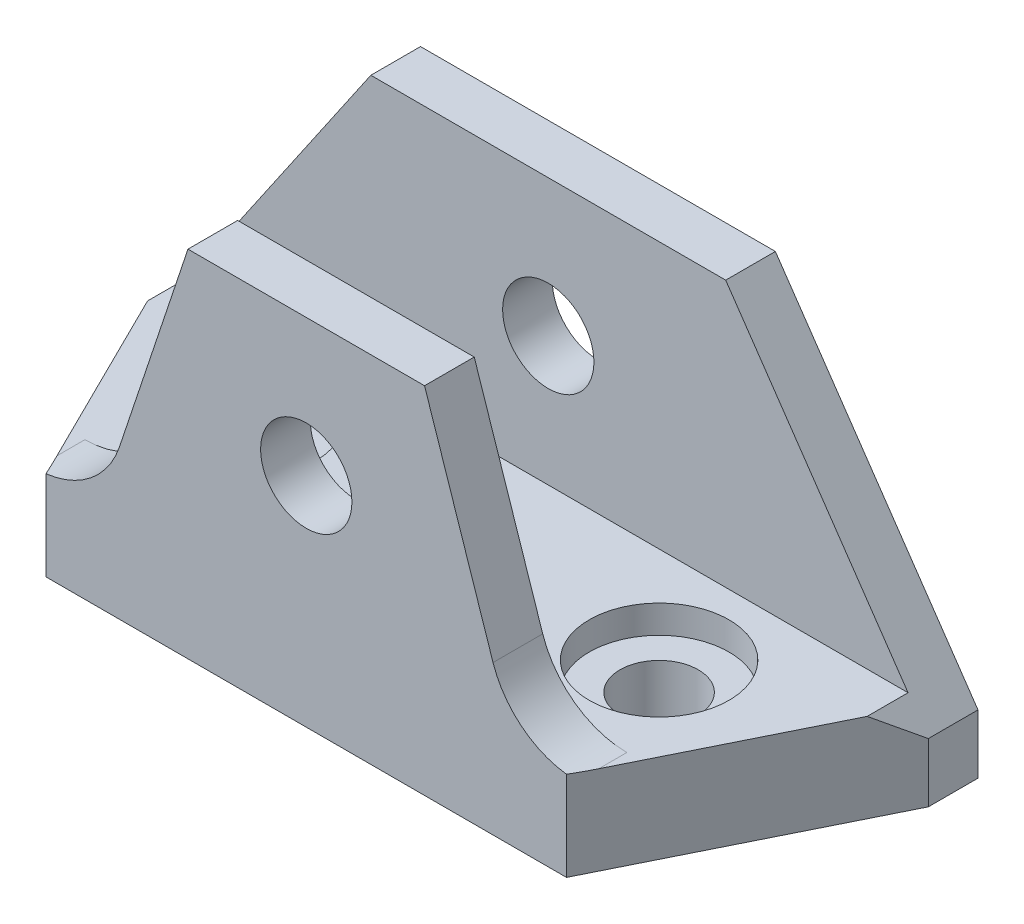
SolidWorks part; units mm, degrees
material "6061-T6 (SS)"
ref_plane "X-Y Datum" through (0, 0, 0) normal (0, 0, 1) x (1, 0, 0)
ref_plane "X-Z Datum" through (0, 0, 0) normal (0, 1, 0) x (1, 0, 0)
ref_plane "Y-Z Datum" through (0, 0, 0) normal (1, 0, 0) x (0, 0, -1)
sketch "Sketch1" plane through (0, 0, 0) normal (0, 1, 0) x (1, 0, 0)
  line L0 (52.0172, 30.5489) -> (33.4988, -6.8632) construction
  line L5 (-55.5625, 37.7114) -> (-33.4988, -6.8632) construction
  line L6 (26.9364, -17.6911) -> (-26.9364, -17.6911)
  line L7 (-26.9364, -17.6911) -> (-44.45, 17.6911)
  line L9 (44.45, 17.6911) -> (26.9364, -17.6911)
  line L10 (44.45, 17.6911) -> (-44.45, 17.6911)
  line L11 (0, 0) -> (0, -50000) construction
  line L12 (0, 0) -> (-50000, 0) construction
  point P6 (-35.6932, 0)
  point P14 (0, 17.6911)
  dimension "D1" = 35.3822
  dimension "D2" = 88.9
extrude "Boss-Extrude1" add sketch "Sketch1" along normal blind 38.1
sketch "Sketch2" plane through (0, 38.1, 0) normal (0, 1, 0) x (1, 0, 0)
  line L1 (-44.45, -10.3251) -> (44.45, -10.3251)
  line L2 (-44.45, -10.3251) -> (-44.45, 10.3251)
  line L3 (-44.45, 10.3251) -> (44.45, 10.3251)
  line L4 (44.45, -10.3251) -> (44.45, 10.3251)
  line L5 (-44.45, -10.3251) -> (44.45, 10.3251) construction
  line L6 (-44.45, 10.3251) -> (44.45, -10.3251) construction
  point P0 (0, 0)
  dimension "D1" = 20.6502
  dimension "D2" = 88.9
extrude "Cut-Extrude1" cut sketch "Sketch2" against normal offset from surface (28.575 mm away) 9.525 up to face at (0, 0, 0)
hole_wizard "CBORE for M8 Hex Head Bolt2" positions "Sketch6" profile "Sketch7" counterbore size "M8" standard "ANSI Metric" end condition through all
sketch "Sketch6" plane through (0, 9.525, 0) normal (0, 1, 0) x (1, 0, 0)
  line L0 (0, 0) -> (0, 50000) construction
  line L1 (0, 0) -> (50000, 0) construction
  point P0 (-22.225, 0)
  point P2 (22.225, 0)
  dimension "D1" = 22.225
  dimension "D2" = 22.225
sketch "Sketch7" plane through (-22.225, 9.525, 0) normal (1, 0, 0) x (0, 0, 1)
  line L0 (0, 0) -> (0, 9.525)
  line L1 (0, 9.525) -> (4.2, 9.525)
  line L3 (4.2, 9.525) -> (4.2, 3)
  line L4 (4.2, 3) -> (7.5, 3)
  line L5 (7.5, 3) -> (7.5, 0)
  line L7 (7.5, 0) -> (0, 0)
  line L11 (0, -6.35) -> (0, 107.95) construction
  dimension "Thru Hole Dia." = 8.4
  dimension "Thru Hole Depth" = 9.525
  dimension "C'Bore Dia." = 15
  dimension "C'Bore Depth" = 3
sketch "Sketch8" plane through (0, 9.525, 0) normal (0, 1, 0) x (1, 0, 0)
  line L0 (-4.1275, 0) -> (4.1275, 0) construction
  line L1 (-4.1275, 8.255) -> (4.1275, 8.255)
  line L2 (-4.1275, -8.255) -> (4.1275, -8.255)
  arc A0 (-4.1275, 8.255) -> (-4.1275, -8.255) centre (-4.1275, 0) ccw
  arc A1 (4.1275, -8.255) -> (4.1275, 8.255) centre (4.1275, 0) ccw
  point P3 (0, 0)
  dimension "D2" = 8.255
  dimension "D1" = 8.255
extrude "Cut-Extrude3" [suppressed] cut sketch "Sketch8" against normal through all
sketch "Sketch9" plane through (0, 0, 10.3251) normal (0, 0, -1) x (-1, 0, 0)
  line L0 (0, 0) -> (50000, 0) construction
  line L1 (0, 0) -> (0, -50000) construction
  line L3 (-30.5824, 9.525) -> (30.5824, 9.525) construction
  line L4 (-22.225, 9.525) -> (-12.7, 38.1)
  line L5 (30.5824, 38.1) -> (-30.5824, 38.1) construction
  line L6 (-12.7, 38.1) -> (12.7, 38.1)
  line L7 (12.7, 38.1) -> (22.225, 9.525)
  line L9 (22.225, 9.525) -> (-22.225, 9.525)
  point P9 (0, 9.525)
  point P16 (0, 38.1)
  dimension "D1" = 25.4
  dimension "D4" = 44.45
extrude "Cut-Extrude4" cut sketch "Sketch9" against normal up to next
fillet "Fillet1" radius 9.525 2 edges at (-22.225, 9.525, 14.0081) (22.225, 9.525, 14.0081)
fillet "Fillet2" [suppressed] radius 3.175
sketch "Sketch10" plane through (0, 0, -17.6911) normal (0, 0, -1) x (-1, 0, 0)
  line L0 (0, 0) -> (0, 50000) construction
  line L1 (-44.45, 0) -> (44.45, 0) construction
  line L2 (0, 0) -> (50000, 0) construction
  line L3 (-19.05, 38.1) -> (19.05, 38.1)
  line L4 (-44.45, 38.1) -> (44.45, 38.1) construction
  line L5 (19.05, 38.1) -> (40.8039, 6.35)
  line L7 (40.8039, 6.35) -> (40.8039, 0)
  line L8 (40.8039, 0) -> (-40.8039, 0)
  line L9 (-40.8039, 0) -> (-40.8039, 6.35)
  line L11 (-40.8039, 6.35) -> (-19.05, 38.1)
  point P4 (0, 0)
  point P11 (0, 38.1)
  line M9 (44.45, 0) -> (44.45, 38.1)
  line M10 (44.45, 38.1) -> (-44.45, 38.1)
  line M11 (-44.45, 38.1) -> (-44.45, 0)
  dimension "D1" = 6.35
  dimension "D2" = 38.1
extrude "Cut-Extrude5" cut sketch "Sketch10" against normal up to next contours L11 M11 M10 | L5 M10 M9
fillet "Fillet3" [suppressed] radius 6.35
sketch3d "3DSketch1"
  line L0 (0, 23.3924, 10.3251) -> (0, 23.3924, -10.3251) construction
  point P5 (0, 23.3924, 0)
  dimension "D1" = 23.3924
hole_wizard "W (0.386) Diameter Hole1" positions "Sketch11" profile "Sketch12" hole size "W" standard "ANSI Inch" end condition through all
sketch "Sketch11" plane through (0, 0, 17.6911) normal (0, 0, 1) x (1, 0, 0)
  line L3 (0, 0) -> (0, -50000) construction
  line L4 (-26.9364, 0) -> (26.9364, 0) construction
  line L5 (0, 0) -> (-49740.8845, 0) construction
  point P0 (0, 23.3924)
  point P15 (0, 0)
sketch "Sketch12" plane through (0, 23.3924, 17.6911) normal (1, 0, 0) x (0, -1, 0)
  line L0 (0, 0) -> (0, 35.3822)
  line L1 (0, 35.3822) -> (4.9022, 35.3822)
  line L2 (4.9022, 35.3822) -> (4.9022, 0)
  line L5 (4.9022, 0) -> (0, 0)
  line L11 (0, -6.35) -> (0, 107.95) construction
  dimension "Thru Hole Dia." = 9.8044
  dimension "Thru Hole Depth" = 35.3822
sketch "Sketch13" [suppressed] plane through (41.3069, 0, 0) normal (1, 0, 0) x (0, 0, -1)
  line L0 (17.6911, 0) -> (17.6911, 2.173)
  line L2 (17.6911, 2.173) -> (-17.6911, 2.173)
  line L3 (-17.6911, 2.173) -> (-17.6911, 0)
  line L4 (-17.6911, 0) -> (17.6911, 0)
  line L5 (-17.6911, 0) -> (-17.6911, 17.5116) construction
  line L7 (17.6911, 0) -> (17.6911, 4.346) construction
extrude "Cut-Extrude6" [suppressed] cut sketch "Sketch13" against normal through all
sketch "Sketch14" plane through (40.8039, 0, 0) normal (1, 0, 0) x (0, 0, -1)
  line L0 (-17.6911, 38.1) -> (-10.3251, 38.1) construction
  line L1 (-17.6911, 0) -> (-15.6591, 0)
  line L2 (-17.6911, 0) -> (-17.6911, 38.1)
  line L3 (-17.6911, 38.1) -> (-15.6591, 38.1)
  line L4 (-15.6591, 0) -> (-15.6591, 38.1)
  line L5 (10.3251, 38.1) -> (17.6911, 38.1) construction
  line L6 (17.6911, 0) -> (15.6591, 0)
  line L7 (17.6911, 0) -> (17.6911, 38.1)
  line L8 (17.6911, 38.1) -> (15.6591, 38.1)
  line L9 (15.6591, 0) -> (15.6591, 38.1)
  dimension "D1" = 2.032
extrude "Cut-Extrude7" cut sketch "Sketch14" against normal up to surface (81.6079 mm away) up to face at (-40.8039, 3.175, -14.0081)
sketch "Sketch15" plane through (0, 0, 15.6591) normal (0, 0, 1) x (1, 0, 0)
  line L0 (0, 38.1) -> (0, 0) construction
  line L1 (-12.7, 38.1) -> (12.7, 38.1) construction
